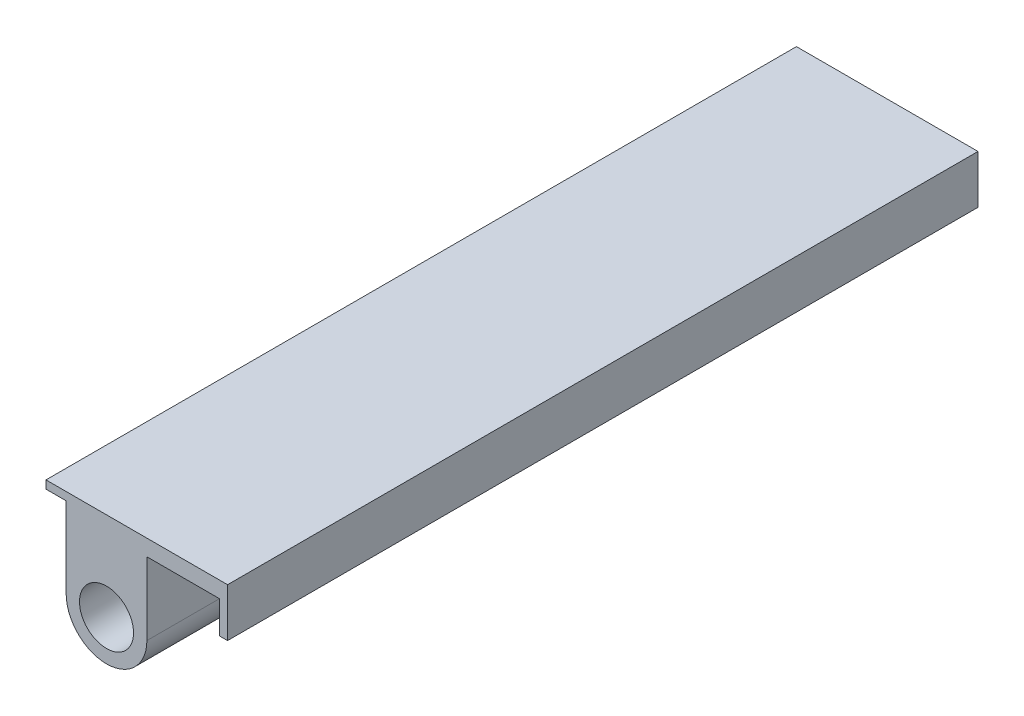
SolidWorks part; units mm, degrees
material "PF"
ref_plane "Спереди" through (0, 0, 0) normal (0, 0, 1) x (1, 0, 0)
ref_plane "Сверху" through (0, 0, 0) normal (0, 1, 0) x (1, 0, 0)
ref_plane "Справа" through (0, 0, 0) normal (1, 0, 0) x (0, 0, -1)
ref_plane "Плоскость4" through (0, 0, 93) normal (0, 0, 1) x (1, 0, 0)
sketch "Эскиз1" plane through (0, 0, 93) normal (0, 0, 1) x (1, 0, 0)
  line L0 (-2.5, 0) -> (0, 0)
  line L1 (0, 0) -> (0, -10)
  line L2 (10, -10) -> (10, -1)
  line L3 (10, -1) -> (19, -1)
  line L4 (19, -1) -> (19, -5)
  line L5 (19, -5) -> (20, -5)
  line L6 (20, -5) -> (20, 1)
  line L7 (20, 1) -> (-2.5, 1)
  line L8 (-2.5, 1) -> (-2.5, 0)
  circle A0 centre (5, -10) radius 3.35
  arc A1 (0, -10) -> (10, -10) centre (5, -10) ccw
extrude "Бобышка-Вытянуть1" add sketch "Эскиз1" against normal blind 93
